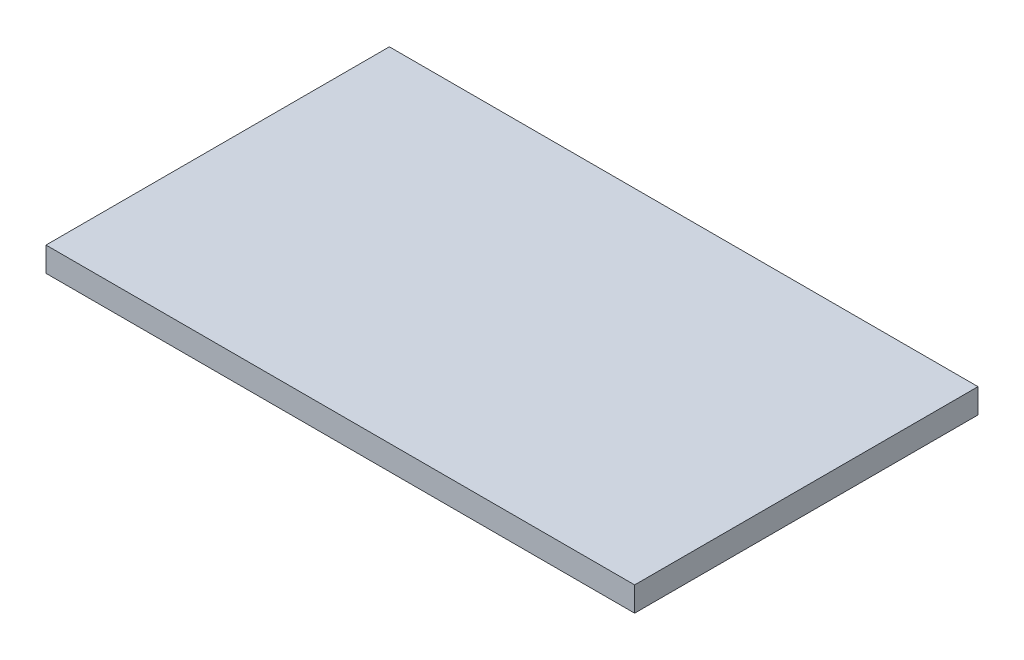
SolidWorks part; units mm, degrees
ref_plane "前视基准面" through (0, 0, 0) normal (0, 0, 1) x (1, 0, 0)
ref_plane "上视基准面" through (0, 0, 0) normal (0, 1, 0) x (1, 0, 0)
ref_plane "右视基准面" through (0, 0, 0) normal (1, 0, 0) x (0, 0, -1)
other "Configuration Table"
sketch "草图1" plane through (0, 0, 0) normal (0, 1, 0) x (1, 0, 0)
  line L1 (0, 0) -> (120, 0)
  line L2 (0, 0) -> (0, -70)
  line L3 (0, -70) -> (120, -70)
  line L4 (120, 0) -> (120, -70)
  dimension "D1" = 70
  dimension "D2" = 120
extrude "凸台-拉伸1" add sketch "草图1" along normal blind 5
